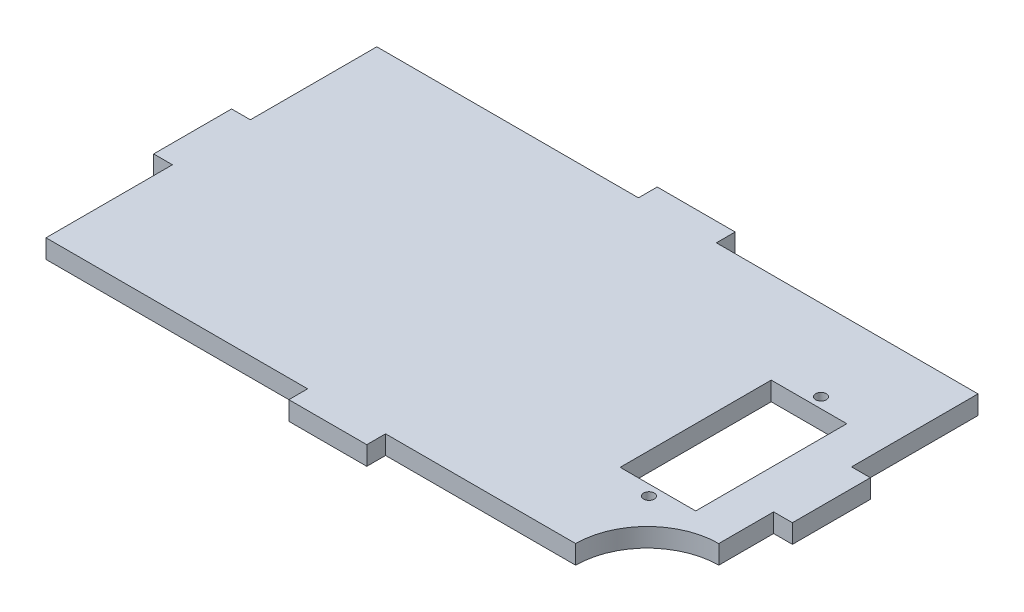
SolidWorks part; units mm, degrees
material "Acrylic (Medium-high impact)"
ref_plane "Front Plane" through (0, 0, 0) normal (0, 0, 1) x (1, 0, 0)
ref_plane "Top Plane" through (0, 0, 0) normal (0, 1, 0) x (1, 0, 0)
ref_plane "Right Plane" through (0, 0, 0) normal (1, 0, 0) x (0, 0, -1)
sketch "Sketch1" plane through (0, 0, 0) normal (0, 1, 0) x (1, 0, 0)
  line L0 (0, 0) -> (0, 20.193)
  line L1 (0, 20.193) -> (-3, 20.193)
  line L2 (0, 52.832) -> (41.783, 52.832)
  line L3 (-3, 32.639) -> (0, 32.639)
  line L4 (0, 32.639) -> (0, 52.832)
  line L5 (54.229, 52.832) -> (96.012, 52.832)
  line L6 (54.229, 52.832) -> (54.229, 55.832)
  line L7 (54.229, 55.832) -> (41.783, 55.832)
  line L8 (41.783, 55.832) -> (41.783, 52.832)
  line L9 (96.012, 0) -> (54.229, 0)
  line L10 (96.012, 52.832) -> (96.012, 32.639)
  line L11 (96.012, 32.639) -> (99.012, 32.639)
  line L12 (99.012, 32.639) -> (99.012, 20.193)
  line L13 (99.012, 20.193) -> (96.012, 20.193)
  line L14 (96.012, 20.193) -> (96.012, 0)
  line L15 (41.783, 0) -> (0, 0)
  line L16 (41.783, 0) -> (41.783, -3)
  line L17 (41.783, -3) -> (54.229, -3)
  line L18 (54.229, -3) -> (54.229, 0)
  line L19 (-3, 32.639) -> (-3, 20.193)
  dimension "D6" = 12.446
  dimension "D1" = 96.012
  dimension "D2" = 52.832
  dimension "D3" = 3
  dimension "D4" = 3
  dimension "D5" = 3
  dimension "D7" = 3
  dimension "D8" = 12.446
  dimension "D9" = 12.446
  dimension "D10" = 12.446
  dimension "D11" = 52.832
extrude "Boss-Extrude1" add sketch "Sketch1" along normal blind 3
sketch "Sketch3" plane through (0, 3, 0) normal (0, 1, 0) x (1, 0, 0)
  line L0 (96.012, 32.639) -> (96.012, 52.832) construction
  line L1 (77.597, 38.227) -> (89.662, 38.227)
  line L2 (77.597, 38.227) -> (77.597, 14.097)
  line L3 (77.597, 14.097) -> (89.662, 14.097)
  line L4 (89.662, 38.227) -> (89.662, 14.097)
  line L5 (96.012, 52.832) -> (54.229, 52.832) construction
  dimension "D1" = 6.35
  dimension "D2" = 14.605
  dimension "D3" = 24.13
  dimension "D4" = 12.065
extrude "Cut-Extrude1" cut sketch "Sketch3" against normal through all
sketch "Sketch4" plane through (0, 3, 0) normal (0, 1, 0) x (1, 0, 0)
  line L0 (54.229, 0) -> (96.012, 0) construction
  line L1 (96.012, 0) -> (96.012, 20.193) construction
  line L2 (96.012, 11.43) -> (96.012, 0)
  line L3 (96.012, 0) -> (84.582, 0)
  arc A0 (84.582, 0) -> (96.012, 11.43) centre (96.012, 0) cw
  dimension "D1" = 11.43
extrude "Cut-Extrude3" cut sketch "Sketch4" against normal through all
sketch "Sketch5" plane through (0, 3, 0) normal (0, 1, 0) x (1, 0, 0)
  line L0 (96.012, 11.43) -> (96.012, 20.193) construction
  line L1 (96.012, 32.639) -> (96.012, 52.832) construction
  line L2 (89.662, 14.097) -> (89.662, 38.227) construction
  circle A0 centre (83.8708, 39.9034) radius 0.8509
  circle A1 centre (83.8708, 12.4206) radius 0.8509
  point P4 (89.662, 26.162)
  dimension "D1" = 1.7018
  dimension "D3" = 27.4828
  dimension "D4" = 13.7414
  dimension "D5" = 12.1412
  dimension "D6" = 12.1412
extrude "Cut-Extrude4" cut sketch "Sketch5" against normal through all
